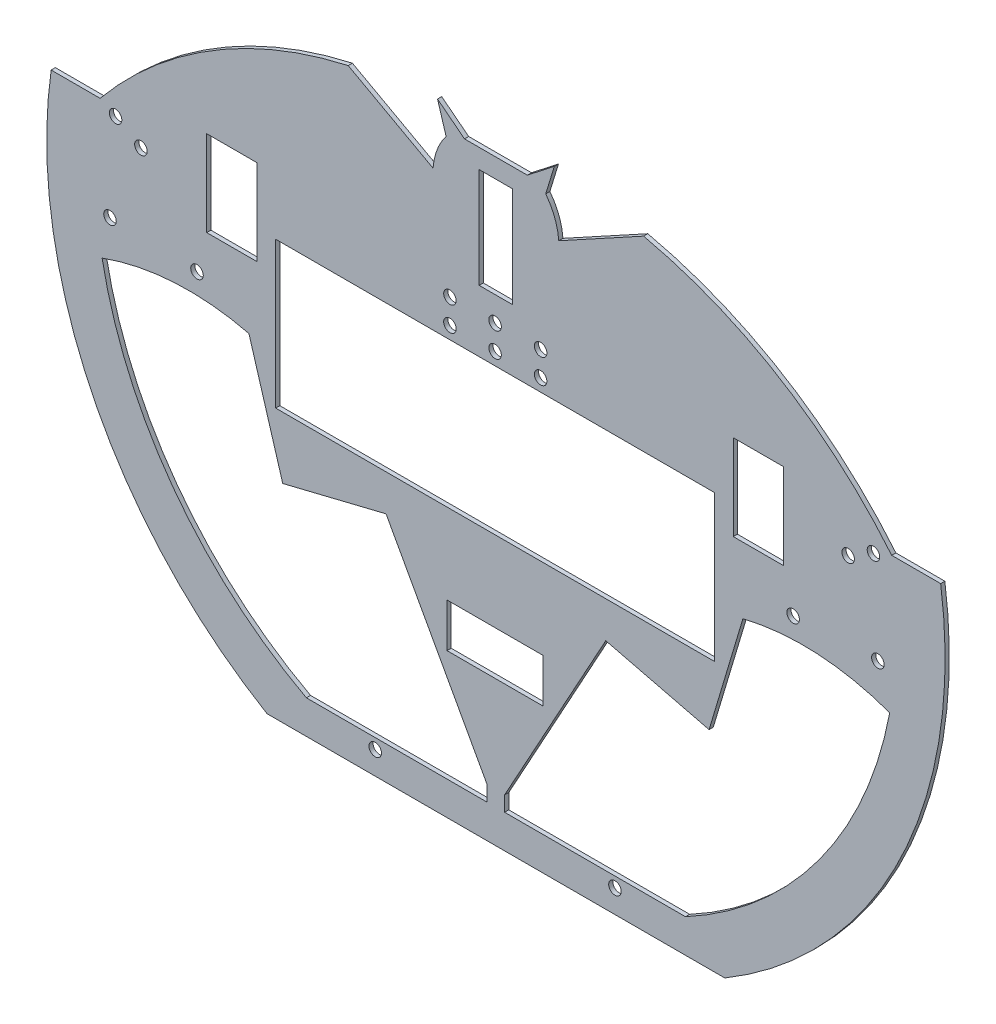
SolidWorks part; units mm, degrees
ref_plane "Alzado" through (0, 0, 0) normal (0, 0, 1) x (1, 0, 0)
ref_plane "Planta" through (0, 0, 0) normal (0, 1, 0) x (1, 0, 0)
ref_plane "Vista lateral" through (0, 0, 0) normal (1, 0, 0) x (0, 0, -1)
sketch "Croquis1" plane through (0, 0, 0) normal (0, 0, 1) x (1, 0, 0)
  line L0 (-1537.1631, -136.7665) -> (-1516.8531, -125.6543)
  line L1 (-1566.1751, -121.8892) -> (-1564.1192, -128.614)
  line L2 (-1559.719, -126.9333) -> (-1566.1751, -121.8892)
  line L3 (-1544.6818, -126.9333) -> (-1559.719, -126.9333)
  line L4 (-1544.6818, -126.9333) -> (-1538.2256, -121.8892)
  line L5 (-1538.2256, -121.8892) -> (-1540.2816, -128.614)
  line L6 (-1550.1238, -261.6933) -> (-1506.8299, -261.6933)
  line L7 (-1506.8299, -261.6933) -> (-1550.1238, -261.6933)
  line L8 (-1578.4888, -214.0311) -> (-1554.277, -258.0965)
  line L9 (-1525.912, -214.0311) -> (-1550.1238, -258.0965)
  line L10 (-1567.2377, -136.7665) -> (-1587.5476, -125.6543)
  line L14 (-1646.9187, -162.1214) -> (-1658.6386, -162.1214)
  line L15 (-1457.482, -162.1214) -> (-1445.9939, -162.1214)
  line L16 (-1563.9002, -224.5825) -> (-1563.9002, -235.0825)
  line L17 (-1563.9002, -224.5825) -> (-1540.9002, -224.5825)
  line L18 (-1540.9002, -224.5825) -> (-1540.9002, -235.0825)
  line L19 (-1563.9002, -235.0825) -> (-1540.9002, -235.0825)
  line L20 (-1495.4002, -177.1979) -> (-1495.4002, -156.6979)
  line L21 (-1495.4002, -156.6979) -> (-1483.4002, -156.6979)
  line L22 (-1483.4002, -177.1979) -> (-1483.4002, -156.6979)
  line L23 (-1483.4002, -177.1979) -> (-1495.4002, -177.1979)
  line L24 (-1621.4002, -156.6979) -> (-1621.4002, -177.1979)
  line L25 (-1609.4002, -156.6979) -> (-1621.4002, -156.6979)
  line L26 (-1609.4002, -177.1979) -> (-1609.4002, -156.6979)
  line L27 (-1621.4002, -177.1979) -> (-1609.4002, -177.1979)
  line L28 (-1556.2004, -131.539) -> (-1556.2004, -155.539)
  line L29 (-1548.2004, -155.539) -> (-1548.2004, -131.539)
  line L30 (-1604.9002, -205.3225) -> (-1499.9002, -205.3225)
  line L31 (-1604.9002, -205.3225) -> (-1604.9002, -170.3225)
  line L32 (-1604.9002, -170.3225) -> (-1499.9002, -170.3225)
  line L33 (-1499.9002, -205.3225) -> (-1499.9002, -170.3225)
  line L34 (-1548.2004, -131.539) -> (-1556.2004, -131.539)
  line L35 (-1548.2004, -155.539) -> (-1556.2004, -155.539)
  line L37 (-1611.3094, -193.0658) -> (-1603.2145, -220.1013)
  line L39 (-1603.2145, -220.1013) -> (-1578.4888, -214.0311)
  line L40 (-1493.0914, -193.0658) -> (-1501.1863, -220.1013)
  line L41 (-1525.912, -214.0311) -> (-1501.1863, -220.1013)
  line L42 (-1445.9939, -162.1214) -> (-1445.7622, -162.1214)
  line L43 (-1552.2004, -269.6933) -> (-1497.4281, -269.6933)
  line L44 (-1552.2004, -269.6933) -> (-1606.9726, -269.6933)
  line L45 (-1554.277, -258.0965) -> (-1554.277, -261.6933)
  line L47 (-1550.1238, -258.0965) -> (-1550.1238, -261.6933)
  line L48 (-1554.277, -261.6933) -> (-1597.5708, -261.6933)
  arc A0 (-1537.1631, -136.7665) -> (-1540.2816, -128.614) centre (-1552.2004, -137.8459) ccw
  arc A1 (-1457.482, -162.1214) -> (-1516.8531, -125.6543) centre (-1540.1202, -230.0985) ccw
  arc A2 (-1564.1192, -128.614) -> (-1567.2377, -136.7665) centre (-1552.2004, -137.8459) ccw
  arc A3 (-1506.8299, -261.6933) -> (-1457.9573, -194.9971) centre (-1552.2004, -177.1933) ccw
  arc A4 (-1646.4434, -194.9971) -> (-1597.5708, -261.6933) centre (-1552.2004, -177.1933) ccw
  arc A5 (-1457.9573, -194.9971) -> (-1493.0914, -193.0658) centre (-1478.6983, -251.7701) ccw
  arc A6 (-1587.5476, -125.6543) -> (-1646.9187, -162.1214) centre (-1564.2806, -230.0985) ccw
  arc A7 (-1611.3094, -193.0658) -> (-1646.4434, -194.9971) centre (-1625.7025, -251.7701) ccw
  arc A8 (-1658.6386, -162.1214) -> (-1606.9726, -269.6933) centre (-1552.2004, -177.1933) ccw
  arc A9 (-1497.4281, -269.6933) -> (-1445.7622, -162.1214) centre (-1552.2004, -177.1933) ccw
  circle A10 centre (-1523.7162, -264.1759) radius 1.5
  circle A11 centre (-1644.5519, -185.6759) radius 1.5
  circle A12 centre (-1541.5028, -167.3225) radius 1.5
  circle A13 centre (-1552.4002, -167.3225) radius 1.5
  circle A14 centre (-1563.2018, -167.3225) radius 1.5
  circle A15 centre (-1552.4002, -161.4725) radius 1.5
  circle A16 centre (-1460.7867, -185.6759) radius 1.5
  circle A17 centre (-1461.8478, -163.9024) radius 1.5
  circle A18 centre (-1643.2203, -164.0149) radius 1.5
  circle A19 centre (-1563.2018, -161.4725) radius 1.5
  circle A20 centre (-1541.5028, -161.4725) radius 1.5
  circle A21 centre (-1581.0838, -264.1759) radius 1.5
  circle A22 centre (-1523.7162, -264.1759) radius 1.5
  circle A23 centre (-1637.1581, -167.5149) radius 1.5
  circle A24 centre (-1467.91, -167.4024) radius 1.5
  circle A25 centre (-1623.732, -186.4855) radius 1.5
  circle A26 centre (-1481.0678, -186.4855) radius 1.5
  circle A27 centre (-1581.0838, -264.1759) radius 1.5
  circle A28 centre (-1523.7162, -264.1759) radius 1.5
extrude "Saliente-Extruir1" add sketch "Croquis1" along normal blind 1 contours L43 A9 L42 L15 A1 L0 A0 L5 L4 L3 L2 L1 A2 L10 A6 L14 A8 L44 A26 A25 A24 A23 A21 A20 A19 A18 A17 A16 A15 A14 A13 A12 A11 A10
